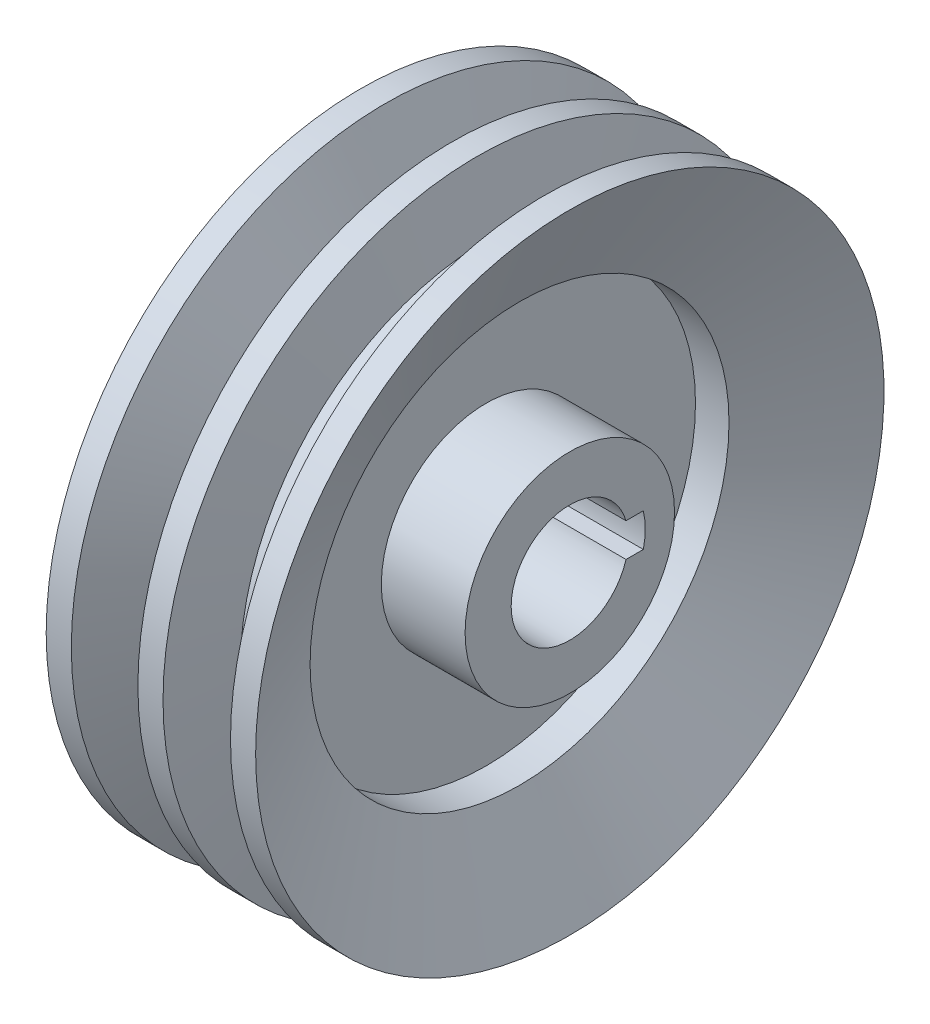
SolidWorks part; units mm, degrees
ref_plane "Alzado" through (0, 0, 0) normal (0, 0, 1) x (1, 0, 0)
ref_plane "Planta" through (0, 0, 0) normal (0, 1, 0) x (1, 0, 0)
ref_plane "Vista lateral" through (0, 0, 0) normal (1, 0, 0) x (0, 0, -1)
sketch "Croquis3" plane through (0, 0, 0) normal (0, 0, 1) x (1, 0, 0)
  line L0 (-127, 139.7) -> (-127, 774.7)
  line L1 (-635, -139.7) -> (635, -139.7)
  line L2 (-635, -139.7) -> (-635, 139.7)
  line L3 (-635, 139.7) -> (-127, 139.7)
  line L4 (635, -139.7) -> (635, 139.7)
  line L5 (-635, -139.7) -> (635, 139.7) construction
  line L6 (-635, 139.7) -> (635, -139.7) construction
  line L8 (127, 774.7) -> (127, 139.7)
  line L9 (127, 139.7) -> (635, 139.7)
  line L10 (-127, 774.7) -> (-330.2, 774.7)
  line L11 (127, 774.7) -> (330.2, 774.7)
  line L13 (-330.2, 774.7) -> (-635, 1409.7)
  line L14 (330.2, 774.7) -> (635, 1409.7)
  line L15 (0, 0) -> (0, 2157.2935) construction
  line L16 (-635, 1409.7) -> (-635, 139.7) construction
  line L17 (635, 1409.7) -> (635, 139.7) construction
  line L18 (-635, 1409.7) -> (-482.6, 1409.7)
  line L20 (635, 1409.7) -> (482.6, 1409.7)
  line L21 (-78.8785, 1409.7) -> (73.5215, 1409.7)
  line L24 (-482.6, 1409.7) -> (-287.528, 1003.3)
  line L26 (482.6, 1409.7) -> (287.528, 1003.3)
  line L29 (-287.528, 1003.3) -> (-135.128, 1003.3)
  line L30 (287.528, 1003.3) -> (135.128, 1003.3)
  line L31 (-78.8785, 1409.7) -> (-135.128, 1003.3)
  line L32 (73.5215, 1409.7) -> (135.128, 1003.3)
  line L33 (-757.8086, -495.3) -> (703.1105, -495.3) construction
  point P0 (0, 0)
  point P26 (-558.8, 1409.7)
  dimension "D1" = 279.4
  dimension "D2" = 1270
  dimension "D3" = 254
  dimension "D4" = 127
  dimension "D5" = 635
  dimension "D6" = 203.2
  dimension "D7" = 1270
  dimension "D8" = 635
  dimension "D9" = 152.4
  dimension "D10" = 152.4
  dimension "D11" = 635
  dimension "D12" = 355.6
  dimension "D13" = 406.4
  dimension "D14" = 406.4
revolve "Revolución1" add sketch "Croquis3" angle 360 about L33
sketch "Croquis4" plane through (635, 0, 0) normal (1, 0, 0) x (0, 0, -1)
  line L0 (340.7768, -393.7) -> (445.7682, -393.7)
  line L1 (340.7768, -596.9) -> (445.7682, -596.9)
  line L2 (-635, -495.3) -> (635, -495.3) construction
  circle A0 centre (0, -495.3) radius 635 construction
  circle A1 centre (0, -495.3) radius 635 construction
  arc A2 (340.7768, -596.9) -> (340.7768, -393.7) centre (0, -495.3) ccw
  circle A3 centre (0, -495.3) radius 355.6 construction
  arc A4 (445.7682, -393.7) -> (445.7682, -596.9) centre (0, -495.3) cw
  dimension "D3" = 101.6
  dimension "D1" = 203.2
  dimension "D2" = 101.6
extrude "Cortar-Extruir2" cut sketch "Croquis4" against normal up to next
